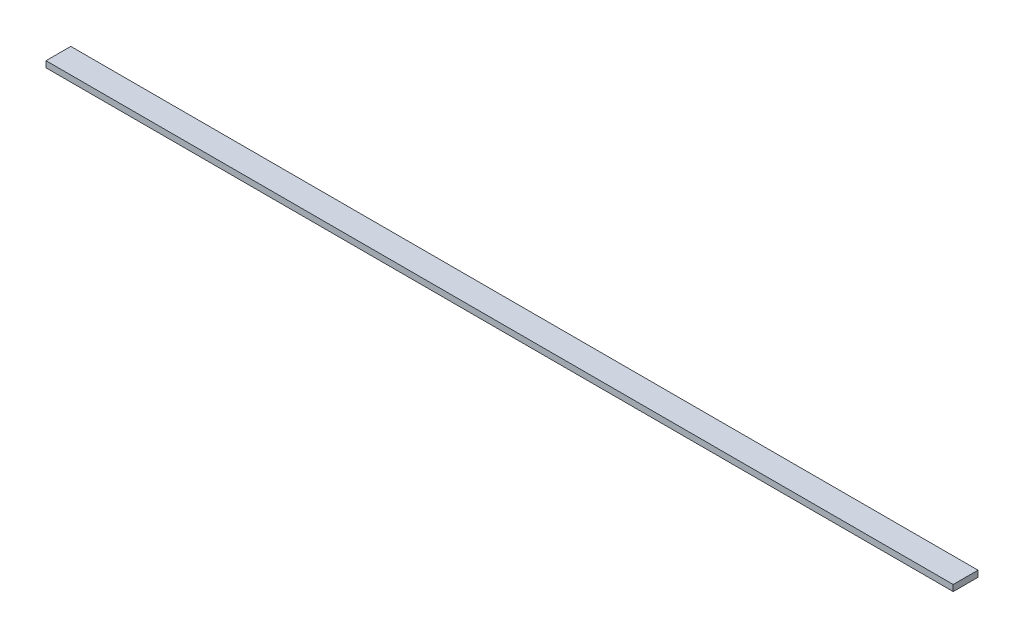
SolidWorks part; units mm, degrees
ref_plane "Front Plane" through (0, 0, 0) normal (0, 0, 1) x (1, 0, 0)
ref_plane "Top Plane" through (0, 0, 0) normal (0, 1, 0) x (1, 0, 0)
ref_plane "Right Plane" through (0, 0, 0) normal (1, 0, 0) x (0, 0, -1)
sketch "Sketch1" plane through (0, 0, 0) normal (0, 1, 0) x (1, 0, 0)
  line L1 (465, 277.5) -> (-465, 277.5)
  line L2 (465, 277.5) -> (465, -277.5)
  line L3 (465, -277.5) -> (-465, -277.5)
  line L4 (-465, 277.5) -> (-465, -277.5)
  line L5 (465, 277.5) -> (-465, -277.5) construction
  line L6 (465, -277.5) -> (-465, 277.5) construction
  line L7 (388.8, 252.1) -> (-388.8, 252.1)
  line L8 (388.8, 252.1) -> (388.8, -252.1)
  line L9 (388.8, -252.1) -> (-388.8, -252.1)
  line L10 (-388.8, 252.1) -> (-388.8, -252.1)
  line L11 (388.8, 252.1) -> (-388.8, -252.1) construction
  line L12 (388.8, -252.1) -> (-388.8, 252.1) construction
  point P0 (0, 0)
  point P6 (0, 0)
  dimension "D1" = 76.2
  dimension "D2" = 555
  dimension "D3" = 25.4
  dimension "D4" = 930
extrude "Boss-Extrude2" add sketch "Sketch1" along normal blind 6.35
sketch "Sketch2" plane through (0, 6.35, 0) normal (0, 1, 0) x (1, 0, 0)
  line L0 (-465, 277.5) -> (-465, -277.5) construction
  line L5 (-465, 252.1) -> (465, 252.1)
  line L6 (-465, 252.1) -> (-465, -277.5)
  line L26 (-465, -277.5) -> (465, -277.5)
  line L27 (465, 252.1) -> (465, -277.5)
  line L28 (388.8, 252.1) -> (-388.8, 252.1) construction
extrude "Cut-Extrude1" cut sketch "Sketch2" against normal through all both and the other way through all
